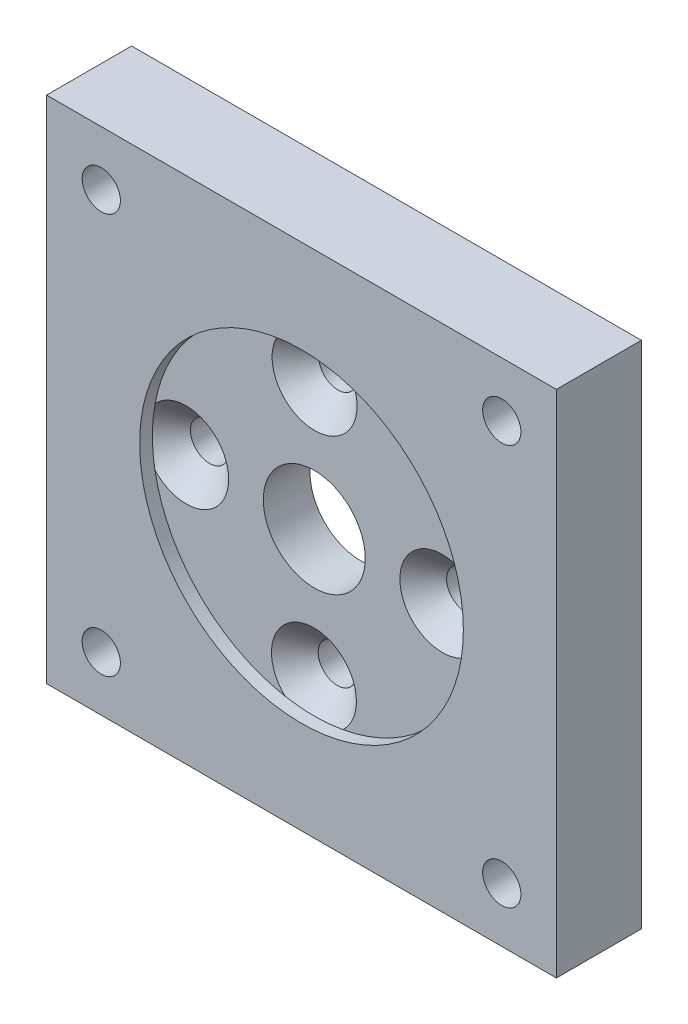
SolidWorks part; units mm, degrees
ref_plane "Front Plane" through (0, 0, 0) normal (0, 0, 1) x (1, 0, 0)
ref_plane "Top Plane" through (0, 0, 0) normal (0, 1, 0) x (1, 0, 0)
ref_plane "Right Plane" through (0, 0, 0) normal (1, 0, 0) x (0, 0, -1)
sketch "Sketch1" plane through (0, 0, 0) normal (0, 0, 1) x (1, 0, 0)
  line L1 (-30, -30) -> (30, -30)
  line L2 (-30, -30) -> (-30, 30)
  line L3 (-30, 30) -> (30, 30)
  line L4 (30, -30) -> (30, 30)
  line L5 (-30, -30) -> (30, 30) construction
  line L6 (-30, 30) -> (30, -30) construction
  point P0 (0, 0)
  dimension "D1" = 60
  dimension "D2" = 60
extrude "Boss-Extrude1" add sketch "Sketch1" along normal blind 10
sketch "Sketch2" plane through (0, 0, 10) normal (0, 0, 1) x (1, 0, 0)
  circle A0 centre (0, 0) radius 6
  dimension "D1" = 12
extrude "Cut-Extrude1" cut sketch "Sketch2" against normal blind 10
sketch "Sketch3" plane through (0, 0, 10) normal (0, 0, 1) x (1, 0, 0)
  circle A0 centre (0, 0) radius 19.05
  dimension "D1" = 38.1
extrude "Cut-Extrude2" cut sketch "Sketch3" against normal blind 1.5
sketch "Sketch4" plane through (0, 0, 10) normal (0, 0, 1) x (1, 0, 0)
  line L0 (-30, 30) -> (-30, -30) construction
  line L1 (30, 30) -> (-30, 30) construction
  line L2 (30, -30) -> (30, 30) construction
  line L3 (-30, -30) -> (30, -30) construction
  circle A0 centre (-23.57, 23.57) radius 2.25
  circle A1 centre (23.57, 23.57) radius 2.25
  circle A2 centre (23.57, -23.57) radius 2.25
  circle A3 centre (-23.57, -23.57) radius 2.25
  dimension "D1" = 4.5
  dimension "D2" = 4.5
  dimension "D3" = 4.5
  dimension "D4" = 4.5
  dimension "D6" = 6.43
  dimension "D7" = 6.43
  dimension "D8" = 6.43
  dimension "D9" = 6.43
  dimension "D10" = 6.43
  dimension "D11" = 6.43
  dimension "D12" = 6.43
  dimension "D5" = 6.43
extrude "Cut-Extrude3" cut sketch "Sketch4" against normal blind 10
hole_wizard "Ø4.5 (4.5) Diameter Hole1" positions "3DSketch1" profile "Sketch5" hole size "Ø4.5" standard "KS"
sketch3d "3DSketch1"
  line L0 (30, 30, 10) -> (-30, 30, 10) construction
  line L1 (-30, 30, 10) -> (-30, -30, 10) construction
  line L2 (-30, -30, 10) -> (30, -30, 10) construction
  line L3 (30, -30, 10) -> (30, 30, 10) construction
  point P0 (-15.0752, 0.0375, 8.5)
  point P2 (15.0752, -0.0375, 8.5)
  point P4 (0.0375, 15.0752, 8.5)
  point P6 (-0.0375, -15.0752, 8.5)
  dimension "D1" = 30
  dimension "D2" = 30
  dimension "D3" = 30
  dimension "D4" = 30
  dimension "D5" = 15
  dimension "D6" = 15
  dimension "D7" = 15
  dimension "D8" = 15
sketch "Sketch5" plane through (-15.0752, 0.0375, 8.5) normal (1, 0, 0) x (0, -1, 0)
  line L0 (0, 0) -> (0, 16.3519)
  line L1 (0, 16.3519) -> (2.25, 15)
  line L2 (2.25, 15) -> (2.25, 2.75)
  line L3 (2.25, 2.75) -> (5, 0)
  line L5 (5, 0) -> (0, 0)
  line L6 (-2.25, 2.75) -> (-5, 0) construction
  line L10 (0, 16.3519) -> (-2.25, 15) construction
  line L11 (0, -6.35) -> (0, 107.95) construction
  dimension "Hole Dia." = 4.5
  dimension "Hole Depth" = 15
  dimension "Near C'Sink Dia." = 10
  dimension "Near C'Sink Angle" = 90
  dimension "Drill Angle" = 118
sketch "Sketch6" plane through (0, 0, 0) normal (0, 0, -1) x (-1, 0, 0)
  circle A0 centre (0, 0) radius 22.4
  dimension "D1" = 44.8
extrude "Cut-Extrude4" cut sketch "Sketch6" against normal blind 3
